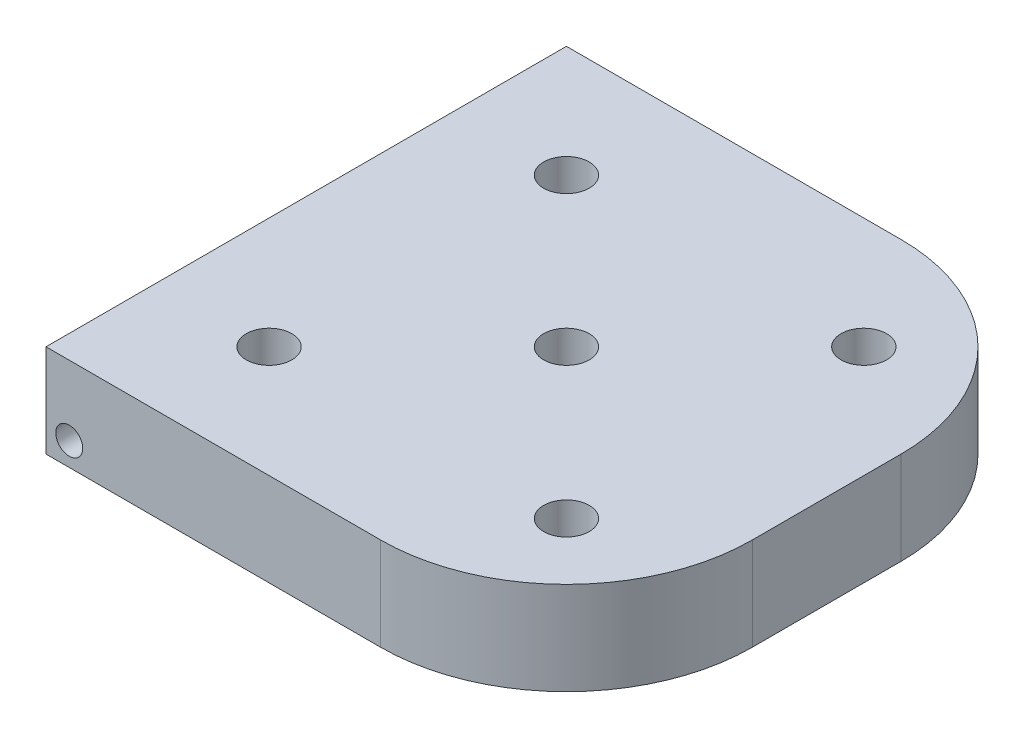
SolidWorks part; units mm, degrees
ref_plane "Front Plane" through (0, 0, 0) normal (0, 0, 1) x (1, 0, 0)
ref_plane "Top Plane" through (0, 0, 0) normal (0, 1, 0) x (1, 0, 0)
ref_plane "Right Plane" through (0, 0, 0) normal (1, 0, 0) x (0, 0, -1)
sketch "Sketch1" plane through (0, 0, 0) normal (0, 1, 0) x (1, 0, 0)
  line L1 (0, 0) -> (56, 0)
  line L2 (0, 0) -> (0, 56)
  line L3 (0, 56) -> (56, 56)
  line L4 (56, 0) -> (56, 56)
  circle A0 centre (28, 28) radius 2.45
  circle A1 centre (12, 44) radius 2.45
  circle A2 centre (44, 44) radius 2.45
  circle A3 centre (44, 12) radius 2.45
  circle A4 centre (12, 12) radius 2.45
  dimension "D3" = 4.9
  dimension "D4" = 4.9
  dimension "D5" = 4.9
  dimension "D6" = 4.9
  dimension "D7" = 4.9
  dimension "D8" = 12
  dimension "D9" = 12
  dimension "D10" = 12
  dimension "D11" = 12
  dimension "D12" = 12
  dimension "D13" = 12
  dimension "D14" = 12
  dimension "D15" = 12
  dimension "D16" = 28
  dimension "D1" = 56
  dimension "D2" = 56
  dimension "23" = 28
extrude "Boss-Extrude1" add sketch "Sketch1" along normal blind 10
sketch "Sketch2" plane through (0, 0, 0) normal (0, 0, 1) x (1, 0, 0)
  line L0 (0, 10) -> (0, 0) construction
  line L1 (0, 0) -> (56, 0) construction
  circle A0 centre (2.5, 2.5) radius 1.45
  dimension "D1" = 2.5
  dimension "D2" = 2.5
extrude "Cut-Extrude1" cut sketch "Sketch2" against normal through all
fillet "Fillet1" radius 20 2 edges at (56, 5, -56) (56, 5, 0)
